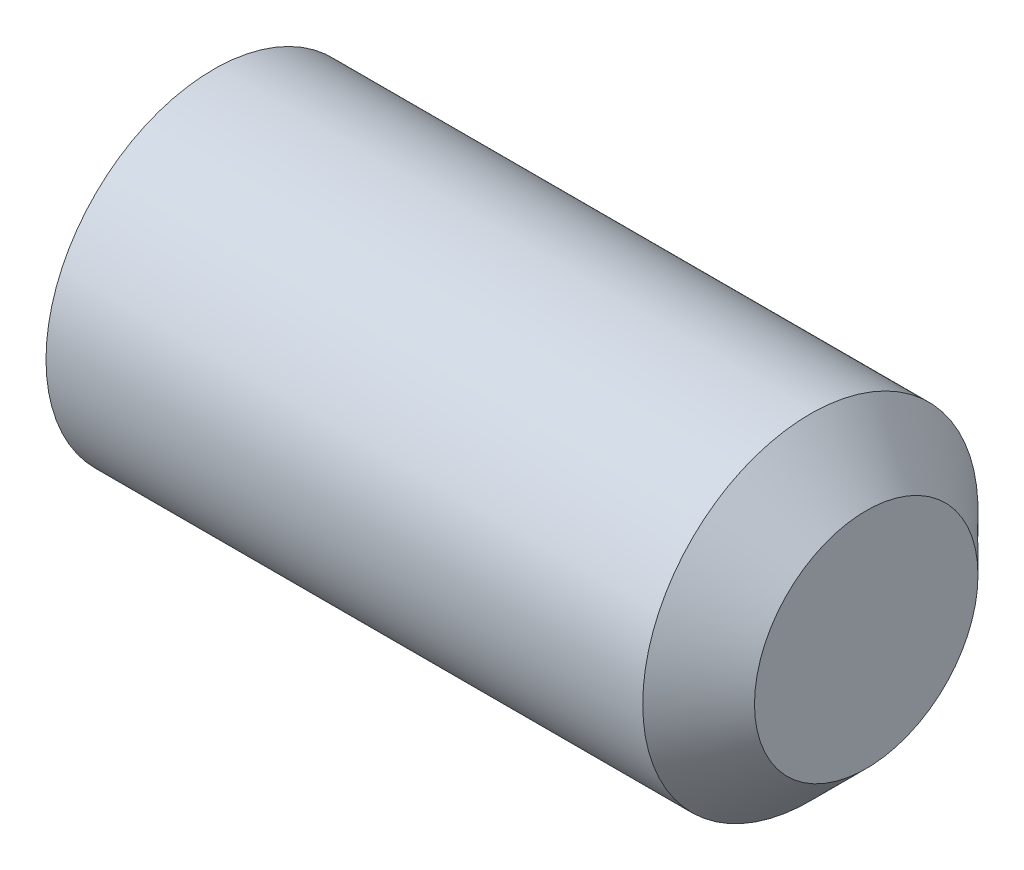
SolidWorks part; units mm, degrees
revolve "BaseBody" add sketch "BodySke" angle 360 about L5
sketch "BodySke" plane through (0, 0, 0) normal (0, 0, 1) x (1, 0, 0)
  line L0 (0, 0) -> (0, 2.4455)
  line L1 (0, 2.4455) -> (0.3201, 3)
  line L2 (0.3201, 3) -> (11, 3)
  line L3 (11, 3) -> (12, 2)
  line L4 (12, 0) -> (0, 0)
  line L5 (-12.7, 0) -> (88.9, 0) construction
  line L6 (12, 2) -> (12, 0)
  line L7 (12, 2) -> (12, 11.525) construction
  line L8 (0, -2.4455) -> (0.3201, -3) construction
  line L9 (1, 15.875) -> (1, -3.175) construction
  line L10 (11, -3) -> (12, -2) construction
  dimension "Diameter" = 6
  dimension "Drive_ch_ang" = 60
  dimension "Minor_dia" = 4.891
  dimension "Cup_nose_ang" = 45
  dimension "Cup_dia" = 4
  dimension "Length" = 12
  dimension "Advance" = 1
cosmetic thread "ThreadCosmetic" parameters "Thread_minor"=4.891
material "AISI 1035 Steel (SS)"
ref_plane "Plane1" through (0, 0, 0) normal (0, 0, 1) x (1, 0, 0)
ref_plane "Plane2" through (0, 0, 0) normal (0, 1, 0) x (1, 0, 0)
ref_plane "Plane3" through (0, 0, 0) normal (1, 0, 0) x (0, 0, -1)
other "Configuration Table"
sketch "Sketch2" plane through (0, 0, 0) normal (-1, 0, 0) x (0, 0, 1)
  line L0 (0.866, 1.5) -> (-0.866, 1.5)
  line L1 (-0.866, 1.5) -> (-1.7321, 0)
  line L2 (0.866, 1.5) -> (1.7321, 0)
  line L3 (0.866, -1.5) -> (1.7321, 0)
  line L4 (0.866, -1.5) -> (-0.866, -1.5)
  line L5 (-0.866, -1.5) -> (-1.7321, 0)
  dimension "Hex_size" = 3
  dimension "D2" = 1.5
  dimension "D3" = 1.5
extrude "Hex" cut sketch "Sketch2" against normal blind 3.5
sketch "ThdSchSke" plane through (0, 0, 0) normal (0, 0, 1) x (1, 0, 0)
  line L0 (0.3201, -2.4455) -> (-0.0681, -3)
  line L1 (0.3201, -2.4455) -> (0.7084, -3)
  line L2 (0.7084, -3) -> (0.7084, -3.75)
  line L3 (-3.175, 0) -> (5.1513, 0) construction
  line L5 (0.7084, -3.75) -> (-0.0681, -3.75)
  line L6 (-0.0681, -3.75) -> (-0.0681, -3)
  line L8 (0.3201, 3) -> (0.3201, -3) construction
  dimension "Thread_minor" = 4.891
  dimension "Diameter" = 6
revolve "ThreadSchematic" [suppressed] cut sketch "ThdSchSke" angle 360 about L3
pattern_linear "ThdSchPat" [suppressed]
equation "\"D2@Sketch2\" = \"Hex_size@Sketch2\" / 2"
equation "\"D3@Sketch2\" = \"Hex_size@Sketch2\" / 2"
equation "\"Thread_minor@ThreadCosmetic\" = \"Minor_dia@BodySke\""
equation "\"Thread_minor@ThdSchSke\" = \"Thread_minor@ThreadCosmetic\""
equation "\"Diameter@ThdSchSke\" = \"Diameter@BodySke\""
equation "\"Overcut@ThdSchSke\" = \"Diameter@BodySke\" * 1.25"
equation "\"Num_threads@ThdSchPat\" = int( (\"Length@BodySke\" - ( ( ( \"Diameter@BodySke\" - \"Minor_dia@BodySke\" ) * 0.5 ) / tan( \"Drive_ch_ang@BodySke\" * 0.017453292 ) ) - ( ( ( \"Diameter@BodySke\" - \"Cup_dia@BodySke\" ) * 0.5 ) * tan( \"Cup_nose_ang@BodySke\" * 0.017453292 ) ) ) / \"Advance@BodySke\" + 0.999 )  + 1"
equation "\"Advance@ThdSchPat\" = (\"Length@BodySke\" - ( ( ( \"Diameter@BodySke\" - \"Minor_dia@BodySke\" ) * 0.5 ) / tan( \"Drive_ch_ang@BodySke\" * 0.017453292 ) ) - ( ( ( \"Diameter@BodySke\" - \"Cup_dia@BodySke\" ) * 0.5 ) * tan( \"Cup_nose_ang@BodySke\" * 0.017453292 ) ) ) /  (\"Num_threads@ThdSchPat\" - 1) 'relax it"
equation "' \"Num_threads@ThdSchPat\" = \"Num_threads@ThdSchPat\" - sgn( \"Num_threads@ThdSchPat\" - 1) '---chamfered tips only---"
